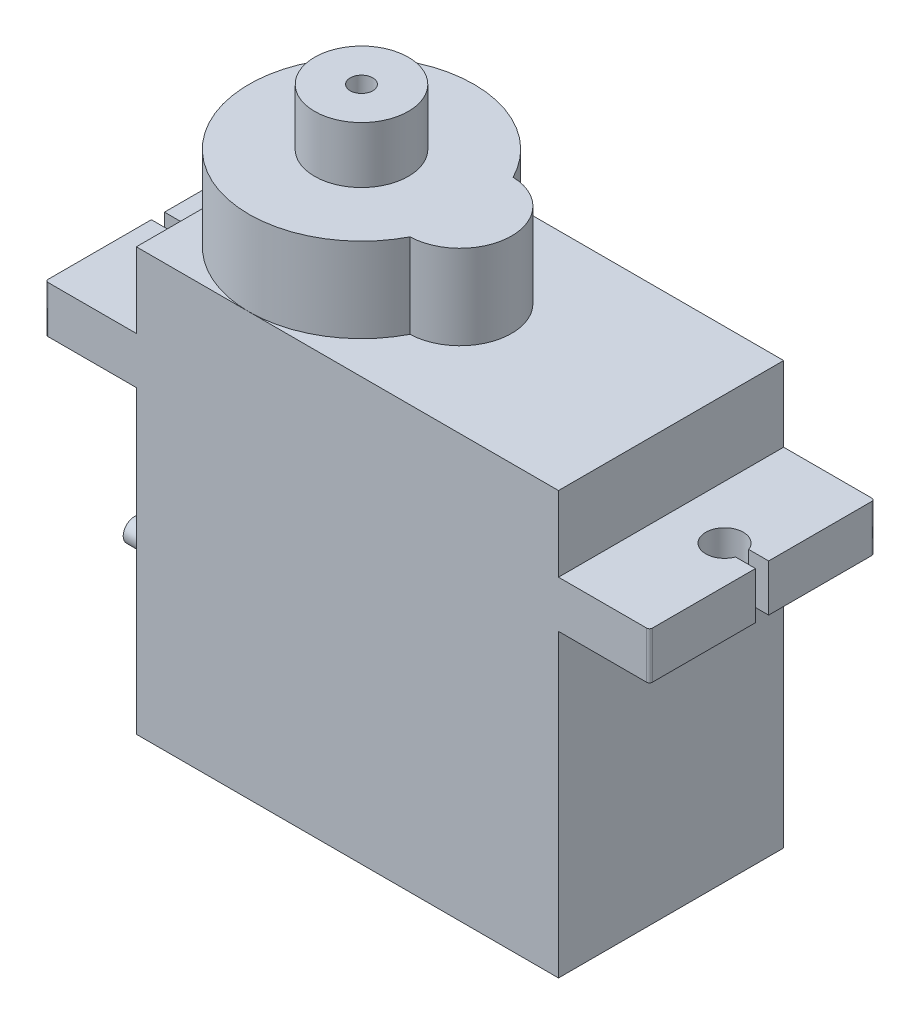
SolidWorks part; units mm, degrees
ref_plane "正面" through (0, 0, 0) normal (0, 0, 1) x (1, 0, 0)
ref_plane "平面" through (0, 0, 0) normal (0, 1, 0) x (1, 0, 0)
ref_plane "右側面" through (0, 0, 0) normal (1, 0, 0) x (0, 0, -1)
sketch "ｽｹｯﾁ2" plane through (0, 0, 0) normal (0, 1, 0) x (1, 0, 0)
  line L0 (0, 0) -> (0, 6) construction
  line L1 (-11.25, -6) -> (11.25, -6)
  line L2 (-11.25, -6) -> (-11.25, 6)
  line L3 (-11.25, 6) -> (11.25, 6)
  line L4 (11.25, -6) -> (11.25, 6)
  line L5 (-11.25, -6) -> (11.25, 6) construction
  line L6 (-11.25, 6) -> (11.25, -6) construction
  line L7 (0, 0) -> (-11.25, 0) construction
  point P0 (0, 0)
  dimension "D1" = 12
  dimension "D2" = 22.5
extrude "ﾎﾞｽ - 押し出し1" add sketch "ｽｹｯﾁ2" against normal blind 22.5
sketch "ｽｹｯﾁ3" plane through (0, 0, 0) normal (0, 1, 0) x (1, 0, 0)
  line L0 (-11.25, 0) -> (11.25, 0) construction
  line L1 (-11.25, 6) -> (-11.25, -6) construction
  line L2 (11.25, -6) -> (11.25, 6) construction
  line L3 (0, 6) -> (0, 0) construction
  line L4 (11.25, 6) -> (-11.25, 6) construction
  circle A0 centre (-5.25, 0) radius 6
  circle A1 centre (0, 0) radius 2.75
  dimension "D1" = 12
  dimension "D2" = 5.5
extrude "ﾎﾞｽ - 押し出し2" add sketch "ｽｹｯﾁ3" along normal blind 4.5 contours A1 A0 | A0 A1 | A0 A1
sketch "ｽｹｯﾁ4" plane through (0, 4.5, 0) normal (0, 1, 0) x (1, 0, 0)
  circle A0 centre (-5.25, 0) radius 2.5
  arc A1 (0.0833, 2.7487) -> (0.0833, -2.7487) centre (-5.25, 0) ccw construction
  dimension "D1" = 5
extrude "ﾎﾞｽ - 押し出し3" add sketch "ｽｹｯﾁ4" along normal blind 3
sketch "ｽｹｯﾁ5" plane through (0, 7.5, 0) normal (0, 1, 0) x (1, 0, 0)
  circle A0 centre (-5.25, 0) radius 0.6
  dimension "D1" = 1.2
extrude "ｶｯﾄ - 押し出し1" cut sketch "ｽｹｯﾁ5" against normal blind 3
ref_plane "平面1" through (0, -4, 0) normal (0, 1, 0) x (1, 0, 0)
sketch "ｽｹｯﾁ6" plane through (0, -4, 0) normal (0, 1, 0) x (1, 0, 0)
  line L0 (11.25, 6) -> (-5.25, 6) construction
  line L1 (-16.1, -6) -> (16.1, -6)
  line L2 (-16.1, -6) -> (-16.1, 6)
  line L3 (-16.1, 6) -> (16.1, 6)
  line L4 (16.1, -6) -> (16.1, 6)
  line L5 (-16.1, -6) -> (16.1, 6) construction
  line L6 (-16.1, 6) -> (16.1, -6) construction
  line L7 (-16.1, 0) -> (16.1, 0) construction
  line L8 (0, 6) -> (0, -6) construction
  line L9 (16.1, -0.35) -> (15.0367, -0.35)
  line L10 (-16.1, -0.35) -> (-15.0367, -0.35)
  line L11 (16.1, 0.35) -> (15.0367, 0.35)
  line L12 (-16.1, 0.35) -> (-15.0367, 0.35)
  arc A0 (15.0367, 0.35) -> (15.0367, -0.35) centre (14.1, 0) ccw
  arc A1 (-15.0367, 0.35) -> (-15.0367, -0.35) centre (-14.1, 0) cw
  point P0 (0, 0)
  dimension "D2" = 2
  dimension "D3" = 2
  dimension "D1" = 32.2
  dimension "D4" = 0.7
extrude "ﾎﾞｽ - 押し出し4" add sketch "ｽｹｯﾁ6" against normal blind 2.5 contours L12 A1 L10 L2 L1 L4 L9 A0 L11 L3
fillet "ﾌｨﾚｯﾄ1" radius 0.15 4 edges at (-16.1, -5.25, -6) (16.1, -5.25, -6) (16.1, -5.25, 6) (-16.1, -5.25, 6)
sketch "ｽｹｯﾁ7" plane through (-11.25, 0, 0) normal (-1, 0, 0) x (0, 0, 1)
  line L0 (-6, -18) -> (6, -18) construction
  line L1 (-6, -22.5) -> (-6, -6.5) construction
  line L2 (6, -22.5) -> (6, -6.5) construction
  line L3 (-6, -22.5) -> (6, -22.5) construction
  line L4 (0, 0) -> (0, -22.5) construction
  arc A0 (-0.55, -18.2398) -> (0.55, -18.2398) centre (0, -18) ccw
  arc A1 (0.55, -18.2398) -> (0.55, -17.7602) centre (1.1, -18) ccw
  arc A2 (-0.55, -18.2398) -> (-0.55, -17.7602) centre (-1.1, -18) cw
  arc A3 (0.55, -17.7602) -> (-0.55, -17.7602) centre (0, -18) ccw
  dimension "D2" = 1.2
  dimension "D4" = 0.6
  dimension "D1" = 4.5
  dimension "D3" = 1.1
extrude "ﾎﾞｽ - 押し出し5" add sketch "ｽｹｯﾁ7" along normal blind 5 contours A3 A2 A0 A1
